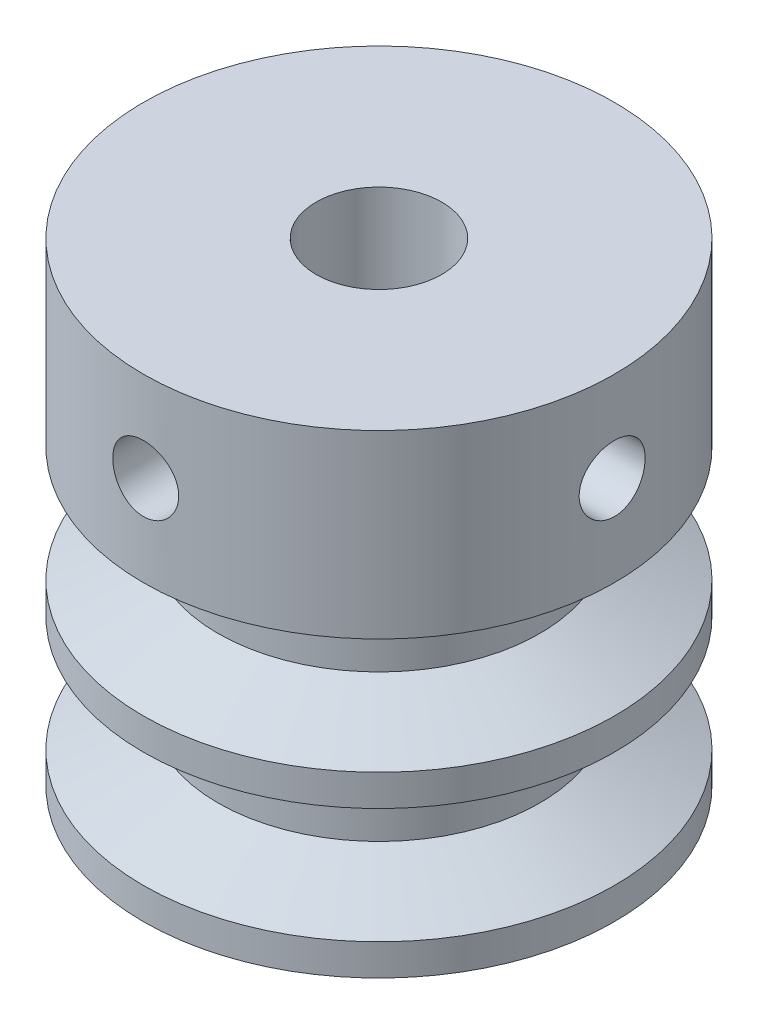
SolidWorks part; units mm, degrees
ref_plane "前视基准面" through (0, 0, 0) normal (0, 0, 1) x (1, 0, 0)
ref_plane "上视基准面" through (0, 0, 0) normal (0, 1, 0) x (1, 0, 0)
ref_plane "右视基准面" through (0, 0, 0) normal (1, 0, 0) x (0, 0, -1)
sketch "草图1" plane through (0, 0, 0) normal (0, 0, 1) x (1, 0, 0)
  line L0 (0, 48.964) -> (0, 0) construction
  line L1 (4, 30.2) -> (15, 30.2)
  line L2 (15, 30.2) -> (15, 18.7)
  line L3 (15, 18.7) -> (10.25, 16.525)
  line L4 (10.25, 16.525) -> (10.25, 13.525)
  line L5 (10.25, 13.525) -> (15, 11.35)
  line L6 (15, 11.35) -> (15, 9.35)
  line L7 (15, 9.35) -> (10.25, 7.175)
  line L8 (10.25, 7.175) -> (10.25, 4.175)
  line L9 (10.25, 4.175) -> (15, 2)
  line L10 (15, 2) -> (15, 0)
  line L11 (15, 0) -> (4, 0)
  line L12 (4, 0) -> (4, 30.2)
  point P5 (14.7669, 5.5515)
  point P16 (14.8691, 14.4473)
  point P17 (14.2418, 3.4701)
  point P18 (10.25, 16.525)
  dimension "D1" = 30.2
  dimension "D2" = 4
  dimension "D3" = 10.25
  dimension "D4" = 11.5
  dimension "D5" = 3
  dimension "D6" = 2
  dimension "D7" = 2
  dimension "D8" = 15
revolve "旋转1" add sketch "草图1" angle 360 about L0
ref_plane "基准面2" through (0, 18.7, 0) normal (0, -1, 0) x (-1, 0, 0)
ref_plane "基准面3" through (0, 24.45, 0) normal (0, -1, 0) x (-1, 0, 0)
sketch "草图3" plane through (0, 24.45, 0) normal (0, -1, 0) x (-1, 0, 0)
  circle A1 centre (0, 0) radius 15
  circle A2 centre (0, 0) radius 15 construction
  point P0 (-15, 0)
  point P1 (0, -15)
  dimension "D1" = 0
hole_wizard "M5 螺纹孔2" positions "3D草图5" profile "草图6" tap size "M5" standard "GB" end condition up to next
sketch3d "3D草图5"
  point P0 (0, 24.45, 15)
  point P3 (15, 24.45, 0)
  point P7 (0, 24.45, 15)
  point P9 (15, 24.45, 0)
  point P12 (0, 0, 0)
  point P13 (0, 0, 0)
sketch "草图6" plane through (15, 24.45, 0) normal (0, 1, 0) x (0, 0, -1)
  line L0 (0, 0) -> (0, 15)
  line L1 (0, 15) -> (2.1, 15)
  line L2 (2.1, 15) -> (2.1, 0)
  line L5 (2.1, 0) -> (0, 0)
  line L11 (0, -6.35) -> (0, 107.95) construction
  dimension "通孔螺纹孔钻头直径" = 4.2
  dimension "通孔螺纹孔钻头深度" = 15
cosmetic thread "孔螺蚊线3"
cosmetic thread "孔螺蚊线4"
cosmetic thread "孔螺蚊线5"
cosmetic thread "孔螺蚊线6"
